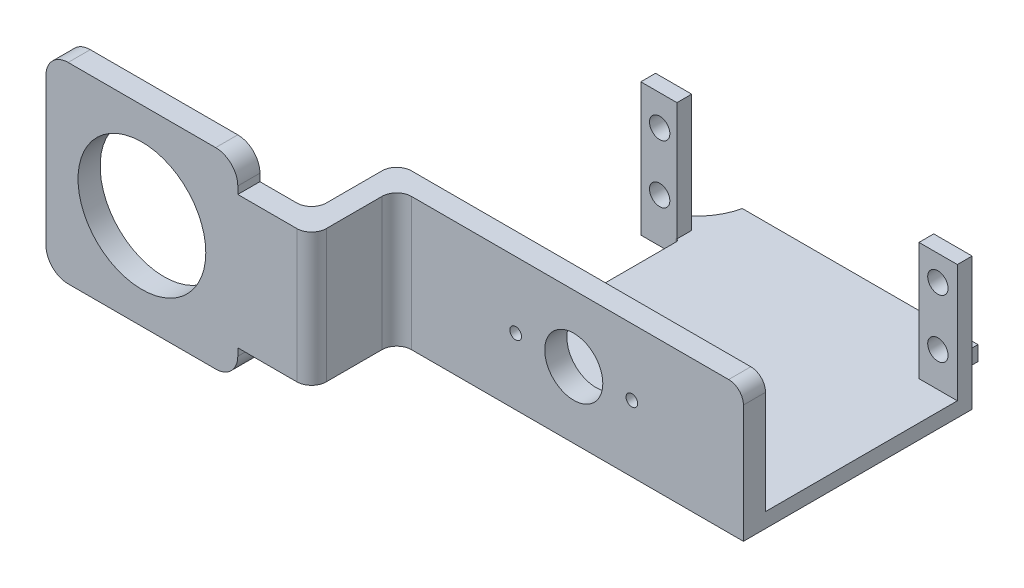
SolidWorks part; units mm, degrees
other "Markup1"
sketch "Sketch5" plane through (-1373.3675, 18.5, -401.6604) normal (0.7238, 0.4704, -0.5049) x (0.4214, -0.8807, -0.2164)
ref_plane "Front Plane" through (0, 0, 0) normal (0, 0, 1) x (1, 0, 0)
ref_plane "Top Plane" through (0, 0, 0) normal (0, 1, 0) x (1, 0, 0)
ref_plane "Right Plane" through (0, 0, 0) normal (1, 0, 0) x (0, 0, -1)
sketch "Sketch2" plane through (0, 0, 0) normal (0, 1, 0) x (1, 0, 0)
  line L1 (-1421.2635, 399.1204) -> (-1373.3675, 399.1204)
  line L2 (-1421.2635, 399.1204) -> (-1421.2635, 371.1804)
  line L3 (-1421.2635, 371.1804) -> (-1373.3675, 371.1804)
  line L4 (-1373.3675, 399.1204) -> (-1373.3675, 371.1804)
  dimension "D1" = 47.896
  dimension "D2" = 27.94
extrude "Boss-Extrude1" add sketch "Sketch2" along normal blind 2.54
sketch "Sketch4" plane through (0, 0, 0) normal (0, -1, 0) x (1, 0, 0)
  line L0 (-1421.2635, -399.1204) -> (-1427.8675, -399.1204)
  line L1 (-1373.3675, -399.1204) -> (-1379.9715, -399.1204)
  line L2 (-1373.3675, -399.1204) -> (-1373.3675, -401.6604)
  line L3 (-1373.3675, -401.6604) -> (-1379.9715, -401.6604)
  line L4 (-1379.9715, -399.1204) -> (-1379.9715, -401.6604)
  line L5 (-1421.2635, -399.1204) -> (-1421.2635, -401.6604)
  line L6 (-1421.2635, -401.6604) -> (-1427.8675, -401.6604)
  line L7 (-1427.8675, -399.1204) -> (-1427.8675, -401.6604)
  line L8 (-1421.2635, -399.1204) -> (-1421.2635, -371.1804) construction
  line L9 (-1373.3675, -399.1204) -> (-1421.2635, -399.1204) construction
  dimension "D1" = 6.604
  dimension "D2" = 2.54
  dimension "D3" = 6.604
  dimension "D4" = 2.54
  dimension "D5" = 0
  dimension "D6" = 0
extrude "Boss-Extrude7" add sketch "Sketch4" against normal blind 22.86
sketch "Sketch22" plane through (0, 0, -399.1204) normal (0, 0, -1) x (-1, 0, 0)
  line L1 (1421.2635, 0) -> (1379.9715, 0)
  line L2 (1421.2635, 0) -> (1421.2635, 2.54)
  line L3 (1421.2635, 2.54) -> (1379.9715, 2.54)
  line L4 (1379.9715, 0) -> (1379.9715, 2.54)
extrude "Boss-Extrude9" add sketch "Sketch22" along normal blind 10.16
sketch "Sketch23" plane through (-1379.9715, 0, 0) normal (1, 0, 0) x (0, 0, -1)
  line L1 (401.6604, 0) -> (409.2804, 0)
  line L2 (401.6604, 0) -> (401.6604, 2.54)
  line L3 (401.6604, 2.54) -> (409.2804, 2.54)
  line L4 (409.2804, 0) -> (409.2804, 2.54)
extrude "Boss-Extrude10" add sketch "Sketch23" along normal blind 6.604
sketch "Sketch24" plane through (-1421.2635, 0, 0) normal (-1, 0, 0) x (0, 0, 1)
  line L1 (-409.2804, 2.54) -> (-401.6604, 2.54)
  line L2 (-409.2804, 2.54) -> (-409.2804, 0)
  line L3 (-409.2804, 0) -> (-401.6604, 0)
  line L4 (-401.6604, 2.54) -> (-401.6604, 0)
extrude "Boss-Extrude11" add sketch "Sketch24" along normal blind 6.604
sketch "Sketch25" plane through (0, 2.54, 0) normal (0, 1, 0) x (1, 0, 0)
  line L0 (-1427.8675, 401.6604) -> (-1427.8675, 409.2804) construction
  line L1 (-1427.8675, 409.2804) -> (-1373.3675, 409.2804) construction
  line L2 (-1420.5538, 409.2804) -> (-1427.8675, 409.2804)
  line L3 (-1427.8675, 409.2804) -> (-1427.8675, 401.6604)
  line L5 (-1373.3675, 409.2804) -> (-1373.3675, 401.6604) construction
  line L6 (-1373.3675, 401.6604) -> (-1379.9715, 401.6604) construction
  line L7 (-1379.9715, 409.2804) -> (-1373.3675, 409.2804)
  line L8 (-1373.3675, 409.2804) -> (-1373.3675, 401.6604)
  arc A0 (-1427.8675, 401.6604) -> (-1420.5538, 409.2804) centre (-1430.4377, 411.4472) ccw
  arc A1 (-1379.9715, 409.2804) -> (-1373.3675, 401.6604) centre (-1372.8595, 408.7724) ccw
extrude "Cut-Extrude2" cut sketch "Sketch25" against normal blind 6.604
sketch "Sketch26" plane through (0, 0, -399.1204) normal (0, 0, 1) x (1, 0, 0)
  line L0 (-1421.2635, 22.86) -> (-1427.8675, 22.86) construction
  line L1 (-1427.8675, 22.86) -> (-1427.8675, 0) construction
  line L2 (-1379.9715, 22.86) -> (-1379.9715, 2.54) construction
  circle A0 centre (-1424.6175, 17.61) radius 1.75
  circle A1 centre (-1424.6175, 7.61) radius 1.75
  circle A2 centre (-1376.7215, 18.5143) radius 1.75
  circle A3 centre (-1376.7215, 8.5143) radius 1.75
  point P12 (0, 0)
  point P15 (-1381.1455, 16.3121)
  point P16 (0, 0)
  dimension "D1" = 3.5
  dimension "D2" = 3.5
  dimension "D3" = 3.5
  dimension "D4" = 3.5
  dimension "D5" = 10
  dimension "D6" = 5.25
  dimension "D7" = 3.25
  dimension "D8" = 3.25
  dimension "D9" = 10
  dimension "D10" = 3.25
  dimension "D11" = 3.25
extrude "Cut-Extrude3" cut sketch "Sketch26" against normal blind 6.604
ref_plane "Plane4" through (-1421.2635, 2.54, -399.1204) normal (0, -1, 0) x (-1, 0, 0)
sketch "Sketch28" plane through (0, 0, -399.1204) normal (0, 0, 1) x (1, 0, 0)
  line L0 (-1426.8515, 2.54) -> (-1415.6755, 2.54) construction
  line L1 (-1421.2635, 22.86) -> (-1421.6445, 22.86)
  line L2 (-1421.2635, 22.86) -> (-1421.2635, 2.54)
  line L3 (-1421.2635, 2.54) -> (-1421.6445, 2.54)
  line L4 (-1421.6445, 22.86) -> (-1421.6445, 2.54)
  dimension "D1" = 0.381
extrude "Cut-Extrude4" cut sketch "Sketch28" against normal blind 6.604
sketch "Sketch29" plane through (0, 0, -371.1804) normal (0, 0, 1) x (1, 0, 0)
  line L1 (-1421.2635, 2.54) -> (-1373.3675, 2.54)
  line L2 (-1421.2635, 2.54) -> (-1421.2635, 0)
  line L3 (-1421.2635, 0) -> (-1373.3675, 0)
  line L4 (-1373.3675, 2.54) -> (-1373.3675, 0)
extrude "Boss-Extrude12" add sketch "Sketch29" along normal blind 5.08
sketch "Sketch31" plane through (0, 0, 0) normal (0, -1, 0) x (1, 0, 0)
  line L1 (-1373.3675, -366.1004) -> (-1436.8675, -366.1004)
  line L2 (-1373.3675, -366.1004) -> (-1373.3675, -362.2904)
  line L3 (-1373.3675, -362.2904) -> (-1436.8675, -362.2904)
  line L4 (-1436.8675, -366.1004) -> (-1436.8675, -362.2904)
  line L5 (-1436.8675, -362.2904) -> (-1433.0575, -362.2904)
  line L6 (-1436.8675, -362.2904) -> (-1436.8675, -351.437)
  line L7 (-1436.8675, -351.437) -> (-1433.0575, -351.437)
  line L8 (-1433.0575, -362.2904) -> (-1433.0575, -351.437)
  line L9 (-1433.0575, -351.437) -> (-1445.7575, -351.437)
  line L10 (-1433.0575, -351.437) -> (-1433.0575, -347.627)
  line L11 (-1433.0575, -347.627) -> (-1445.7575, -347.627)
  line L12 (-1445.7575, -351.437) -> (-1445.7575, -347.627)
  line M11 (-1373.3675, -366.1004) -> (-1421.2635, -366.1004)
  dimension "D1" = 63.5
  dimension "D2" = 3.81
  dimension "D3" = 3.81
  dimension "D4" = 3.81
  dimension "D5" = 12.7
extrude "Boss-Extrude13" add sketch "Sketch31" against normal blind 22.86 contours L4 L1 L2 L3 M11 | L3 L8 L7 L6 | L12 L9 L7 L10 L11
sketch "Sketch32" plane through (-1445.7575, 0, 0) normal (-1, 0, 0) x (0, 0, 1)
  line L0 (-351.437, 22.86) -> (-347.627, 22.86) construction
  line L1 (-351.437, 27.94) -> (-347.627, 27.94)
  line L2 (-351.437, 27.94) -> (-351.437, -5.08)
  line L3 (-351.437, -5.08) -> (-347.627, -5.08)
  line L4 (-347.627, 27.94) -> (-347.627, -5.08)
  line L5 (-351.437, 0) -> (-347.627, 0) construction
  line L6 (-347.627, 22.86) -> (-347.627, 0) construction
  dimension "D1" = 3.81
  dimension "D2" = 5.08
  dimension "D3" = 5.08
  dimension "D4" = 0
extrude "Boss-Extrude14" add sketch "Sketch32" along normal blind 33.02
sketch "Sketch33" plane through (0, 0, -362.2904) normal (0, 0, 1) x (1, 0, 0)
  line L0 (-1373.3675, 22.86) -> (-1433.0575, 22.86) construction
  line L1 (-1373.3675, 22.86) -> (-1373.3675, 0) construction
  circle A0 centre (-1402.5775, 11.43) radius 5
  circle A2 centre (-1412.5775, 11.43) radius 1
  circle A3 centre (-1392.5775, 11.43) radius 1
  point P6 (0, 0)
  point P8 (-1406.0125, 22.86)
  dimension "D1" = 10
  dimension "D2" = 2
  dimension "D3" = 2
  dimension "D4" = 10
  dimension "D5" = 10
  dimension "D6" = 11.43
  dimension "D7" = 29.21
extrude "Cut-Extrude5" cut sketch "Sketch33" against normal blind 9.144
sketch "Sketch34" plane through (0, 0, -347.627) normal (0, 0, 1) x (1, 0, 0)
  line L2 (-1478.7775, -5.08) -> (-1478.7775, 27.94) construction
  line L4 (-1478.7775, 27.94) -> (-1445.7575, 27.94) construction
  circle A0 centre (-1462.2675, 11.43) radius 11
  point P6 (-1466.8043, 27.94)
  dimension "D1" = 22
  dimension "D2" = 16.51
  dimension "D3" = 16.51
extrude "Cut-Extrude6" cut sketch "Sketch34" against normal blind 9.144
fillet "Fillet6" radius 2.54 6 edges at (-1421.2635, 1.27, -366.1004) (-1436.8675, 11.43, -351.437) (-1436.8675, 11.43, -366.1004) (-1373.3675, 22.86, -364.1954) (-1433.0575, 11.43, -362.2904) (-1433.0575, 11.43, -347.627)
fillet "Fillet7" radius 3.81 4 edges at (-1445.7575, 27.94, -349.532) (-1445.7575, -5.08, -349.532) (-1478.7775, 27.94, -349.532) (-1478.7775, -5.08, -349.532)
sketch "Sketch35" plane through (0, 2.54, 0) normal (0, 1, 0) x (1, 0, 0)
  line L4 (-1421.2635, 399.1204) -> (-1421.7715, 399.1204)
  line L5 (-1421.2635, 399.1204) -> (-1421.2635, 398.6124)
  line L6 (-1421.2635, 399.1204) -> (-1421.2635, 368.6404) construction
  arc A1 (-1421.7715, 399.1204) -> (-1421.2635, 398.6124) centre (-1421.7715, 398.6124) cw
  dimension "D1" = 0.508
  dimension "D2" = 0.508
extrude "Boss-Extrude15" add sketch "Sketch35" against normal blind 2.54
